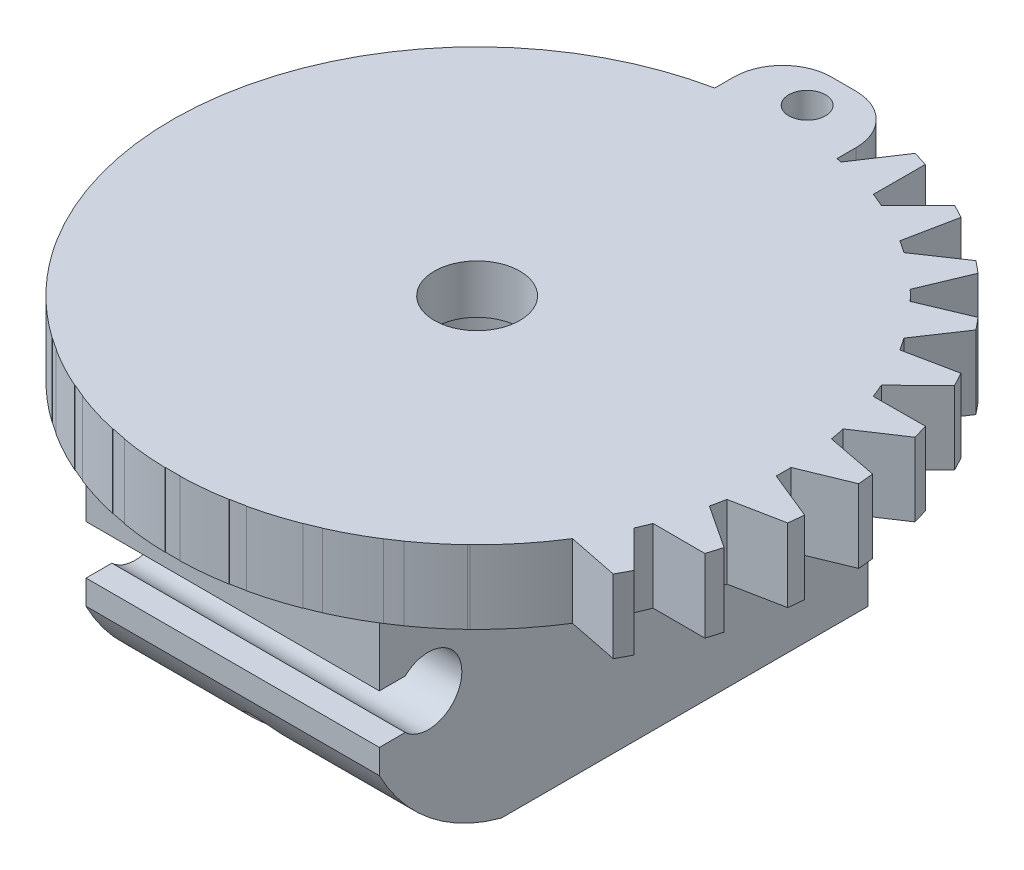
SolidWorks part; units mm, degrees
ref_plane "Front Plane" through (0, 0, 0) normal (0, 0, 1) x (1, 0, 0)
ref_plane "Top Plane" through (0, 0, 0) normal (0, 1, 0) x (1, 0, 0)
ref_plane "Right Plane" through (0, 0, 0) normal (1, 0, 0) x (0, 0, -1)
sketch "Sketch1" plane through (0, 0, 0) normal (0, 1, 0) x (1, 0, 0)
  circle A0 centre (0, 0) radius 5.5
  dimension "D1" = 11
extrude "Boss-Extrude1" add sketch "Sketch1" along normal blind 7
sketch "Sketch2" plane through (0, 7, 0) normal (0, 1, 0) x (1, 0, 0)
  circle A0 centre (0, 0) radius 3
  dimension "D1" = 6
extrude "Cut-Extrude1" cut sketch "Sketch2" against normal blind 5
sketch "Sketch3" plane through (0, 0, 0) normal (0, -1, 0) x (1, 0, 0)
  circle A0 centre (0, 0) radius 10.5
  dimension "D1" = 21
extrude "Boss-Extrude2" add sketch "Sketch3" along normal blind 3
sketch "Sketch4" plane through (0, -3, 0) normal (0, -1, 0) x (1, 0, 0)
  line L0 (2.7362, 12.158) -> (3.9105, 13.9242)
  line L3 (4.516, 13.7405) -> (4.5046, 11.6221)
  line L4 (5.0634, 11.3908) -> (6.5597, 12.8939)
  line L5 (7.1178, 12.5956) -> (6.6933, 10.5201)
  line L6 (7.1962, 10.1843) -> (8.957, 11.3666)
  line L7 (9.4462, 10.9651) -> (8.6249, 9.0124)
  line L8 (9.0527, 8.5848) -> (11.0103, 9.401)
  line L9 (11.4117, 8.9118) -> (10.2253, 7.1567)
  line L10 (0.304, 12.4565) -> (1.1112, 14.4178)
  line L11 (1.7409, 14.3558) -> (2.143, 12.2759)
  line L12 (10.5614, 6.654) -> (12.6406, 7.0725)
  line L13 (12.9389, 6.5144) -> (11.4329, 5.0245)
  line L14 (11.6645, 4.4658) -> (13.7854, 4.4707)
  line L15 (13.9691, 3.8651) -> (12.2013, 2.6977)
  line L16 (12.3195, 2.1046) -> (14.4006, 1.6956)
  line L17 (14.4626, 1.0658) -> (12.5011, 0.2657)
  line L18 (12.5012, -0.3391) -> (14.4625, -1.1462)
  line L19 (14.4005, -1.776) -> (12.3206, -2.1781)
  line L20 (12.2027, -2.7713) -> (13.9689, -3.9456)
  line L21 (13.7852, -4.5511) -> (11.6668, -4.5397)
  line L22 (11.4355, -5.0985) -> (12.9386, -6.5948)
  line L23 (12.6403, -7.1529) -> (10.5648, -6.7284)
  line L24 (10.229, -7.2313) -> (11.4113, -8.9921)
  line L25 (11.0098, -9.4813) -> (9.0571, -8.66)
  line L26 (8.6295, -9.0878) -> (9.4457, -11.0454)
  line L27 (8.9565, -11.4468) -> (7.2014, -10.2604)
  line L28 (6.6987, -10.5965) -> (7.1172, -12.6757)
  line L29 (6.5591, -12.974) -> (5.0692, -11.468)
  line L30 (4.5105, -11.6996) -> (4.5154, -13.8205)
  line L31 (3.9098, -14.0042) -> (2.7424, -12.2364)
  line L32 (2.1493, -12.3546) -> (1.7403, -14.4357)
  line L33 (1.1105, -14.4977) -> (0.3104, -12.5362)
  line L34 (-0.2944, -12.5363) -> (-1.1015, -14.4976)
  line L35 (-1.7313, -14.4356) -> (-2.1334, -12.3557)
  line L36 (-2.7266, -12.2378) -> (-3.9009, -14.004)
  line L37 (-4.5064, -13.8203) -> (-4.495, -11.7019)
  line L38 (-5.0538, -11.4706) -> (-6.5501, -12.9737)
  line L39 (-7.1082, -12.6754) -> (-6.6837, -10.5999)
  line L40 (-7.1866, -10.264) -> (-8.9474, -11.4464)
  line L41 (-9.4366, -11.0449) -> (-8.6153, -9.0922)
  line L42 (-9.0431, -8.6646) -> (-11.0007, -9.4807)
  line L43 (-11.4021, -8.9915) -> (-10.2157, -7.2365)
  line L44 (-10.5518, -6.7337) -> (-12.631, -7.1523)
  line L45 (-12.9293, -6.5942) -> (-11.4233, -5.1043)
  line L46 (-11.6549, -4.5456) -> (-13.7758, -4.5505)
  line L47 (-13.9595, -3.9449) -> (-12.1917, -2.7775)
  line L48 (-12.3099, -2.1843) -> (-14.391, -1.7754)
  line L49 (-14.453, -1.1456) -> (-12.4915, -0.3455)
  line L50 (-12.4916, 0.2593) -> (-14.4529, 1.0665)
  line L51 (-14.3909, 1.6962) -> (-12.311, 2.0983)
  line L52 (-12.1931, 2.6915) -> (-13.9593, 3.8658)
  line L53 (-13.7756, 4.4713) -> (-11.6572, 4.4599)
  line L54 (-11.4259, 5.0187) -> (-12.929, 6.515)
  line L55 (-12.6307, 7.0731) -> (-10.5552, 6.6486)
  line L56 (-10.2193, 7.1515) -> (-11.4017, 8.9123)
  line L57 (-11.0002, 9.4015) -> (-9.0475, 8.5802)
  line L58 (-8.6199, 9.008) -> (-9.436, 10.9656)
  line L59 (-8.9468, 11.367) -> (-7.1918, 10.1806)
  line L60 (-6.689, 10.5167) -> (-7.1076, 12.5959)
  line L61 (-6.5495, 12.8942) -> (-5.0596, 11.3882)
  line L62 (-4.5009, 11.6198) -> (-4.5058, 13.7407)
  line L63 (-3.9002, 13.9244) -> (-2.7328, 12.1566)
  line L64 (-2.1397, 12.2748) -> (-1.7307, 14.3559)
  line L65 (-1.1009, 14.4179) -> (-0.3008, 12.4564)
  arc A3 (1.7409, 14.3558) -> (1.1112, 14.4178) centre (0.0048, -0.0399) ccw
  arc A5 (4.516, 13.7405) -> (3.9105, 13.9242) centre (0.0048, -0.0399) ccw
  arc A7 (7.1178, 12.5956) -> (6.5597, 12.8939) centre (0.0048, -0.0399) ccw
  arc A9 (9.4462, 10.9651) -> (8.957, 11.3666) centre (0.0048, -0.0399) ccw
  arc A11 (11.4117, 8.9118) -> (11.0103, 9.401) centre (0.0048, -0.0399) ccw
  arc A13 (12.9389, 6.5144) -> (12.6406, 7.0725) centre (0.0048, -0.0399) ccw
  arc A15 (13.9691, 3.8651) -> (13.7854, 4.4707) centre (0.0048, -0.0399) ccw
  arc A17 (14.4626, 1.0658) -> (14.4006, 1.6956) centre (0.0048, -0.0399) ccw
  arc A19 (14.4005, -1.776) -> (14.4625, -1.1462) centre (0.0048, -0.0399) ccw
  arc A21 (13.7852, -4.5511) -> (13.9689, -3.9456) centre (0.0048, -0.0399) ccw
  arc A23 (12.6403, -7.1529) -> (12.9386, -6.5948) centre (0.0048, -0.0399) ccw
  arc A25 (11.0098, -9.4813) -> (11.4113, -8.9921) centre (0.0048, -0.0399) ccw
  arc A27 (8.9565, -11.4468) -> (9.4457, -11.0454) centre (0.0048, -0.0399) ccw
  arc A29 (6.5591, -12.974) -> (7.1172, -12.6757) centre (0.0048, -0.0399) ccw
  arc A31 (3.9098, -14.0042) -> (4.5154, -13.8205) centre (0.0048, -0.0399) ccw
  arc A33 (1.1105, -14.4977) -> (1.7403, -14.4357) centre (0.0048, -0.0399) ccw
  arc A35 (-1.7313, -14.4356) -> (-1.1015, -14.4976) centre (0.0048, -0.0399) ccw
  arc A37 (-4.5064, -13.8203) -> (-3.9009, -14.004) centre (0.0048, -0.0399) ccw
  arc A39 (-7.1082, -12.6754) -> (-6.5501, -12.9737) centre (0.0048, -0.0399) ccw
  arc A41 (-9.4366, -11.0449) -> (-8.9474, -11.4464) centre (0.0048, -0.0399) ccw
  arc A43 (-11.4021, -8.9915) -> (-11.0007, -9.4807) centre (0.0048, -0.0399) ccw
  arc A45 (-12.9293, -6.5942) -> (-12.631, -7.1523) centre (0.0048, -0.0399) ccw
  arc A47 (-13.9595, -3.9449) -> (-13.7758, -4.5505) centre (0.0048, -0.0399) ccw
  arc A49 (-14.453, -1.1456) -> (-14.391, -1.7754) centre (0.0048, -0.0399) ccw
  arc A51 (-14.3909, 1.6962) -> (-14.4529, 1.0665) centre (0.0048, -0.0399) ccw
  arc A53 (-13.7756, 4.4713) -> (-13.9593, 3.8658) centre (0.0048, -0.0399) ccw
  arc A55 (-12.6307, 7.0731) -> (-12.929, 6.515) centre (0.0048, -0.0399) ccw
  arc A57 (-11.0002, 9.4015) -> (-11.4017, 8.9123) centre (0.0048, -0.0399) ccw
  arc A59 (-8.9468, 11.367) -> (-9.436, 10.9656) centre (0.0048, -0.0399) ccw
  arc A61 (-6.5495, 12.8942) -> (-7.1076, 12.5959) centre (0.0048, -0.0399) ccw
  arc A63 (-3.9002, 13.9244) -> (-4.5058, 13.7407) centre (0.0048, -0.0399) ccw
  arc A65 (-1.1009, 14.4179) -> (-1.7307, 14.3559) centre (0.0048, -0.0399) ccw
  arc A67 (-4.5009, 11.6198) -> (-5.0596, 11.3882) centre (0.0048, -0.0399) ccw
  arc A70 (-2.1397, 12.2748) -> (-2.7328, 12.1566) centre (0.0048, -0.0399) ccw
  arc A71 (0.304, 12.4565) -> (-0.3008, 12.4564) centre (0.0048, -0.0399) ccw
  arc A72 (2.7362, 12.158) -> (2.143, 12.2759) centre (0.0048, -0.0399) ccw
  arc A73 (5.0634, 11.3908) -> (4.5046, 11.6221) centre (0.0048, -0.0399) ccw
  arc A74 (7.1962, 10.1843) -> (6.6933, 10.5201) centre (0.0048, -0.0399) ccw
  arc A75 (9.0527, 8.5848) -> (8.6249, 9.0124) centre (0.0048, -0.0399) ccw
  arc A76 (10.5614, 6.654) -> (10.2253, 7.1567) centre (0.0048, -0.0399) ccw
  arc A77 (11.6645, 4.4658) -> (11.4329, 5.0245) centre (0.0048, -0.0399) ccw
  arc A78 (12.3195, 2.1046) -> (12.2013, 2.6977) centre (0.0048, -0.0399) ccw
  arc A79 (12.5012, -0.3391) -> (12.5011, 0.2657) centre (0.0048, -0.0399) ccw
  arc A80 (-6.689, 10.5167) -> (-7.1918, 10.1806) centre (0.0048, -0.0399) ccw
  arc A81 (-8.6199, 9.008) -> (-9.0475, 8.5802) centre (0.0048, -0.0399) ccw
  arc A82 (-10.2193, 7.1515) -> (-10.5552, 6.6486) centre (0.0048, -0.0399) ccw
  arc A83 (-11.4259, 5.0187) -> (-11.6572, 4.4599) centre (0.0048, -0.0399) ccw
  arc A84 (-12.1931, 2.6915) -> (-12.311, 2.0983) centre (0.0048, -0.0399) ccw
  arc A85 (-12.3099, -2.1843) -> (-12.1917, -2.7775) centre (0.0048, -0.0399) ccw
  arc A86 (-11.6549, -4.5456) -> (-11.4233, -5.1043) centre (0.0048, -0.0399) ccw
  arc A87 (-9.0431, -8.6646) -> (-8.6153, -9.0922) centre (0.0048, -0.0399) ccw
  arc A88 (-7.1866, -10.264) -> (-6.6837, -10.5999) centre (0.0048, -0.0399) ccw
  arc A89 (-5.0538, -11.4706) -> (-4.495, -11.7019) centre (0.0048, -0.0399) ccw
  arc A90 (-10.5518, -6.7337) -> (-10.2157, -7.2365) centre (0.0048, -0.0399) ccw
  arc A91 (-2.7266, -12.2378) -> (-2.1334, -12.3557) centre (0.0048, -0.0399) ccw
  arc A92 (-0.2944, -12.5363) -> (0.3104, -12.5362) centre (0.0048, -0.0399) ccw
  arc A93 (2.1493, -12.3546) -> (2.7424, -12.2364) centre (0.0048, -0.0399) ccw
  arc A94 (4.5105, -11.6996) -> (5.0692, -11.468) centre (0.0048, -0.0399) ccw
  arc A95 (6.6987, -10.5965) -> (7.2014, -10.2604) centre (0.0048, -0.0399) ccw
  arc A96 (8.6295, -9.0878) -> (9.0571, -8.66) centre (0.0048, -0.0399) ccw
  arc A97 (10.229, -7.2313) -> (10.5648, -6.7284) centre (0.0048, -0.0399) ccw
  arc A98 (11.4355, -5.0985) -> (11.6668, -4.5397) centre (0.0048, -0.0399) ccw
  arc A99 (12.2027, -2.7713) -> (12.3206, -2.1781) centre (0.0048, -0.0399) ccw
  arc A100 (-12.4916, 0.2593) -> (-12.4915, -0.3455) centre (0.0048, -0.0399) ccw
  point P132 (0.0048, -0.0399)
  dimension "D1" = 32
  dimension "D2" = 14.5
  dimension "D3" = 12.5
extrude "Boss-Extrude3" add sketch "Sketch4" against normal blind 3 separate body
sketch "Sketch6" plane through (0, -3, 0) normal (0, -1, 0) x (1, 0, 0)
  line L1 (-6, 10) -> (6, 10)
  line L2 (-6, 10) -> (-6, -10)
  line L3 (-6, -10) -> (6, -10)
  line L4 (6, 10) -> (6, -10)
  line L5 (0, -11) -> (0, 11) construction
  line L6 (11, 0) -> (-11, 0) construction
  dimension "D1" = 12
  dimension "D2" = 20
  dimension "D3" = 6
  dimension "D4" = 10
extrude "Boss-Extrude4" add sketch "Sketch6" along normal blind 10
sketch "Sketch7" plane through (-6, 0, 0) normal (-1, 0, 0) x (0, 0, 1)
  line L0 (10, -13) -> (10, -3) construction
  line L1 (10, -3) -> (-10, -3) construction
  line L3 (8, -7) -> (10, -7)
  line L4 (8, -7) -> (8, -6)
  line L5 (8, -6) -> (10, -6)
  line L6 (10, -7) -> (10, -6)
  line L7 (8, -7) -> (10, -7)
  line L8 (8, -7) -> (8, -8)
  line L9 (8, -8) -> (10, -8)
  line L10 (10, -7) -> (10, -8)
  circle A0 centre (8, -7) radius 1.375
  line M9 (10, -13) -> (10, -3)
  dimension "D1" = 2
  dimension "D5" = 2.75
  dimension "D2" = 4
  dimension "D3" = 2
  dimension "D4" = 1
extrude "Cut-Extrude3" cut sketch "Sketch7" against normal through all both and the other way through all contours L5 A0 L9 L8 L4 | L9 A0 L3 L8 | L3 A0 L5 L4 | A0 L9 L7 M9 | A0 L7 L5 M9
sketch "Sketch8" plane through (-6, 0, 0) normal (-1, 0, 0) x (0, 0, 1)
  line L0 (10, -13) -> (10, -8) construction
  line L1 (10, -13) -> (-10, -13) construction
  line L2 (10, -9) -> (10, -13)
  line L3 (5, -13) -> (10, -13)
  arc A0 (10, -9) -> (5, -13) centre (3.0305, -5.4131) cw
  dimension "D1" = 1
  dimension "D2" = 5
extrude "Cut-Extrude4" cut sketch "Sketch8" against normal through all both and the other way through all
sketch "Sketch10" plane through (0, 0, -10) normal (0, 0, -1) x (-1, 0, 0)
  line L0 (0, 11) -> (0, -11) construction
  line L1 (-0.3104, -3) -> (-1.1105, -3) construction
  circle A0 centre (0, -11) radius 0.75
  dimension "D2" = 1.5
  dimension "D1" = 8
extrude "Cut-Extrude6" cut sketch "Sketch10" against normal through all both and the other way through all
sketch "Sketch12" plane through (0, -3, 0) normal (0, -1, 0) x (1, 0, 0)
  line L2 (0, -11) -> (0, 11) construction
  line L3 (10.5552, 6.6486) -> (12.6418, 8.7351)
  line L4 (2.7128, -12.1761) -> (3.3416, -14.9984)
  arc A7 (10.5552, 6.6486) -> (2.7128, -12.1761) centre (0, 0) ccw
  arc A9 (12.6418, 8.7351) -> (3.3416, -14.9984) centre (0, 0) ccw
extrude "Cut-Extrude9" cut sketch "Sketch12" against normal blind 10
sketch "Sketch14" plane through (0, -3, 0) normal (0, -1, 0) x (1, 0, 0)
  line L0 (11, 0) -> (-11, 0) construction
  line L1 (-2.5, 0) -> (2.5, 0)
  line L2 (-2.5, 0) -> (-2.5, -13)
  line L3 (-0.5, -15) -> (0.5, -15)
  line L4 (2.5, 0) -> (2.5, -13)
  line L5 (0, -11) -> (0, 11) construction
  arc A0 (0.5, -15) -> (2.5, -13) centre (0.5, -13) ccw
  arc A1 (-0.5, -15) -> (-2.5, -13) centre (-0.5, -13) cw
  circle A2 centre (0, -13.5) radius 0.75
  dimension "D4" = 2
  dimension "D5" = 1.5
  dimension "D6" = 1.5
  dimension "D1" = 5
  dimension "D2" = 2.5
  dimension "D3" = 15
extrude "Boss-Extrude5" add sketch "Sketch14" against normal up to surface (3 mm away) up to face at (0, 0, 5.5)
sketch "Sketch15" plane through (0, 7, 0) normal (0, 1, 0) x (1, 0, 0)
  circle A0 centre (0, 0) radius 7.2124
extrude "Cut-Extrude10" cut sketch "Sketch15" against normal up to surface (7 mm away) and the other way through all up to face at (0, 0, 5.5)
sketch "Sketch16" plane through (0, 0, 0) normal (0, 1, 0) x (1, 0, 0)
  circle A0 centre (0, 0) radius 1.5
  circle A1 centre (0, 0) radius 3
  dimension "D1" = 6
extrude "Boss-Extrude6" add sketch "Sketch16" along normal blind 3
sketch "Sketch5" plane through (0, -3, 0) normal (0, -1, 0) x (1, 0, 0)
  circle A0 centre (0, 0) radius 3
  dimension "D1" = 6
extrude "Cut-Extrude2" cut sketch "Sketch5" against normal through all both and the other way through all
sketch "Sketch17" plane through (0, 0, 0) normal (0, 1, 0) x (1, 0, 0)
  circle A0 centre (0, 0) radius 3
  circle A1 centre (0, 0) radius 1.75
  dimension "D1" = 3.5
extrude "Boss-Extrude7" add sketch "Sketch17" against normal blind 2
scale "Scale1" bodies to scale 154 scale about centroid uniform scaling yes scale factor 1.02
